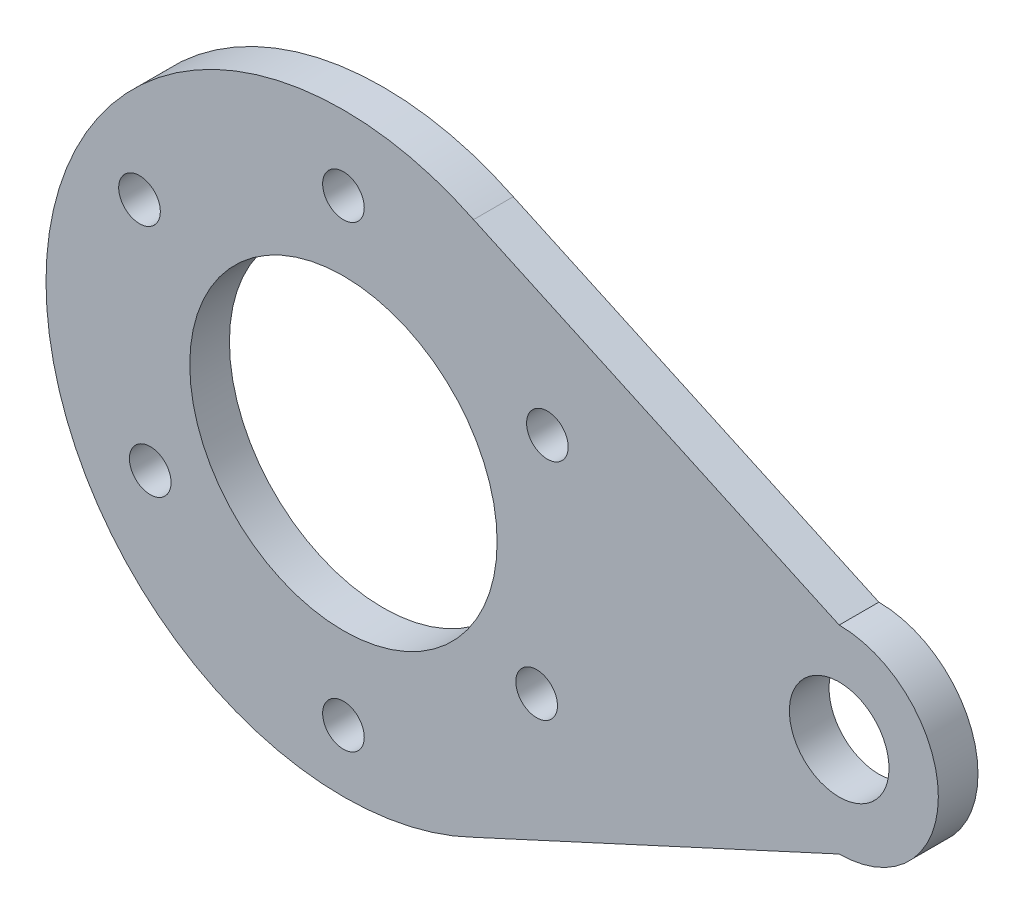
SolidWorks part; units mm, degrees
ref_plane "前视基准面" through (0, 0, 0) normal (0, 0, 1) x (1, 0, 0)
ref_plane "上视基准面" through (0, 0, 0) normal (0, 1, 0) x (1, 0, 0)
ref_plane "右视基准面" through (0, 0, 0) normal (1, 0, 0) x (0, 0, -1)
sketch "草图2" plane through (0, 0, 0) normal (0, 0, 1) x (1, 0, 0)
  line L0 (2.5741, -5.5276) -> (41.8465, -28.2015) construction
  line L1 (2.5741, -5.5276) -> (52.5741, -5.5276) construction
  line L5 (52.5741, 4.4724) -> (15.6991, 21.449)
  line L6 (15.6991, -32.5041) -> (52.5741, -15.5276)
  circle A0 centre (2.5741, -5.5276) radius 23.75 construction
  circle A1 centre (2.5741, -5.5276) radius 22.5 construction
  circle A2 centre (2.5741, -29.2776) radius 2.1
  circle A3 centre (22.0596, -16.7776) radius 2.1
  circle A4 centre (2.5741, -5.5276) radius 30 construction
  arc A5 (15.6991, 21.449) -> (15.6991, -32.5041) centre (2.5741, -5.5276) ccw
  circle A6 centre (2.5741, -5.5276) radius 15.5
  circle A11 centre (52.5741, -5.5276) radius 5.025
  circle A12 centre (52.5741, -5.5276) radius 10 construction
  arc A13 (52.5741, 4.4724) -> (52.5741, -15.5276) centre (52.5741, -5.5276) cw
  circle A14 centre (-17.994, 6.3474) radius 2.1
  circle A15 centre (23.1422, 6.3474) radius 2.1
  circle A16 centre (2.5741, 16.9724) radius 2.1
  circle A17 centre (-16.9115, -16.7776) radius 2.1
  point P10 (0, 0)
  point P26 (0, 0)
  point P27 (0, 0)
  point P31 (0, 0)
  dimension "D1" = 45
  dimension "D2" = 4.2
  dimension "D3" = 50
  dimension "D4" = 60
  dimension "D5" = 10.05
  dimension "D6" = 47.5
  dimension "D7" = 3
  dimension "D8" = 3
extrude "凸台-拉伸1" add sketch "草图2" along normal blind 4
